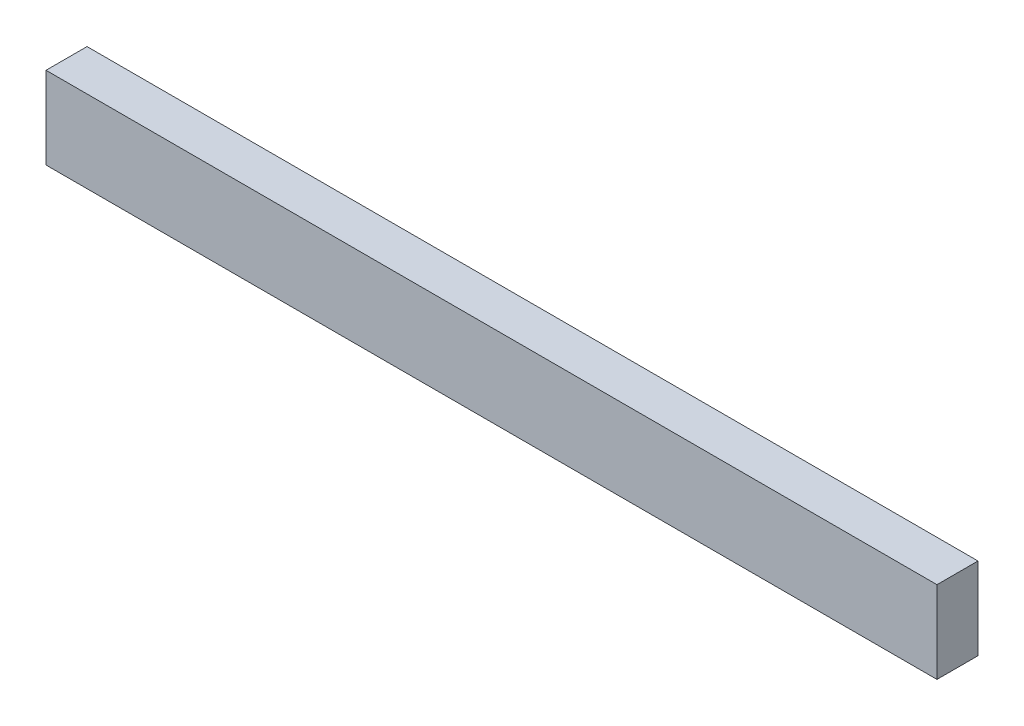
SolidWorks part; units mm, degrees
ref_plane "Front Plane" through (0, 0, 0) normal (0, 0, 1) x (1, 0, 0)
ref_plane "Top Plane" through (0, 0, 0) normal (0, 1, 0) x (1, 0, 0)
ref_plane "Right Plane" through (0, 0, 0) normal (1, 0, 0) x (0, 0, -1)
sketch "Sketch1" plane through (0, 0, 0) normal (0, 0, 1) x (1, 0, 0)
  line L1 (0, 0) -> (-120.65, 0)
  line L2 (0, 0) -> (0, 11.1125)
  line L3 (0, 11.1125) -> (-120.65, 11.1125)
  line L4 (-120.65, 0) -> (-120.65, 11.1125)
  dimension "D1" = 11.1125
  dimension "D2" = 120.65
extrude "Boss-Extrude1" add sketch "Sketch1" along normal blind 5.5562
